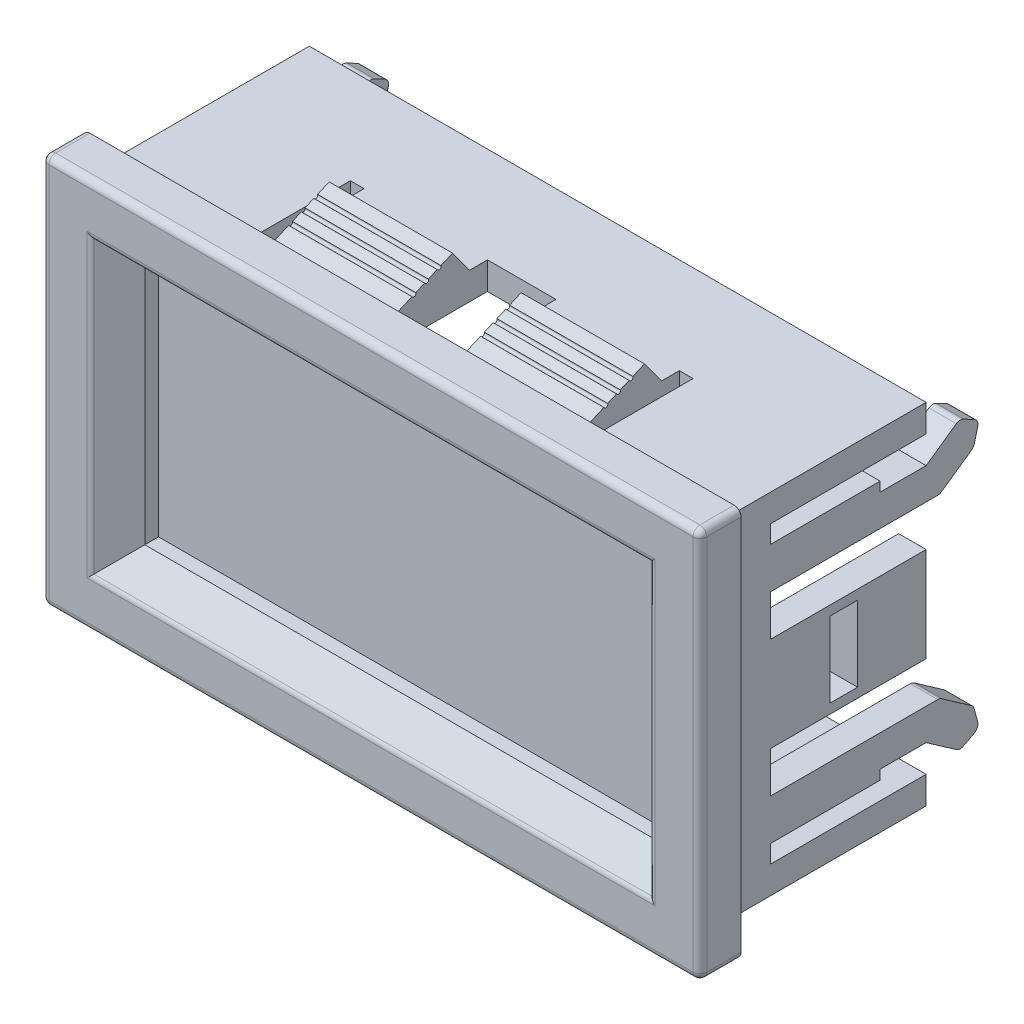
SolidWorks part; units mm, degrees
ref_plane "Front Plane" through (0, 0, 0) normal (0, 0, 1) x (1, 0, 0)
ref_plane "Top Plane" through (0, 0, 0) normal (0, 1, 0) x (1, 0, 0)
ref_plane "Right Plane" through (0, 0, 0) normal (1, 0, 0) x (0, 0, -1)
sketch "Sketch1" plane through (0, 0, 0) normal (0, 0, 1) x (1, 0, 0)
  line L0 (2, 23.5) -> (43, 23.5)
  line L1 (0, 0) -> (45, 0)
  line L2 (0, 0) -> (0, 25.5)
  line L3 (0, 25.5) -> (45, 25.5)
  line L4 (45, 0) -> (45, 25.5)
  line L5 (43, 2) -> (43, 23.5)
  line L6 (2, 2) -> (43, 2)
  line L7 (2, 2) -> (2, 23.5)
  dimension "D1" = 45
  dimension "D2" = 25.5
  dimension "D3" = 2
extrude "Boss-Extrude1" add sketch "Sketch1" along normal blind 15 contours L3 L4 L1 L2 | L0 L5 L6 L7
sketch "Sketch2" plane through (0, 0, 15) normal (0, 0, 1) x (1, 0, 0)
  line L4 (41, 21.5) -> (4, 21.5)
  line L5 (4, 21.5) -> (4, 4)
  line L9 (4, 4) -> (41, 4)
  line L10 (41, 4) -> (41, 21.5)
  line L11 (-1.5, 27) -> (-1.5, -1.5)
  line L12 (-1.5, -1.5) -> (46.5, -1.5)
  line L13 (46.5, -1.5) -> (46.5, 27)
  line L14 (46.5, 27) -> (-1.5, 27)
  line L15 (-1.5, 27) -> (-1.5, -1.5)
  line L16 (-1.5, -1.5) -> (46.5, -1.5)
  line L17 (46.5, -1.5) -> (46.5, 27)
  line L18 (46.5, 27) -> (-1.5, 27)
  dimension "D1" = 1.5
  dimension "D2" = 5.5
extrude "Boss-Extrude2" add sketch "Sketch2" along normal blind 3 contours L18 L15 L16 L17 | L4 L5 L9 L10
fillet "Fillet1" radius 0.5 4 edges at (46.5, 27, 16.5) (46.5, -1.5, 16.5) (-1.5, -1.5, 16.5) (-1.5, 27, 16.5)
fillet "Fillet2" radius 0.5 8 edges at (46.3536, -1.3536, 18) (-1.3536, -1.3536, 18) (-1.3536, 26.8536, 18) (46.3536, 26.8536, 18) (-1.5, 12.75, 18) (22.5, -1.5, 18) (22.5, 27, 18) (46.5, 12.75, 18)
chamfer "Chamfer1" distance 2 angle 45 4 edges at (41, 12.75, 18) (22.5, 21.5, 18) (4, 12.75, 18) (22.5, 4, 18)
fillet "Fillet3" radius 0.5 4 edges at (43, 12.75, 18) (22.5, 23.5, 18) (2, 12.75, 18) (22.5, 2, 18)
sketch "Sketch3" plane through (0, 0, 15) normal (0, 0, -1) x (-1, 0, 0)
  line L8 (-42, 3) -> (-3, 3)
  line L9 (-3, 3) -> (-3, 22.5)
  line L10 (-3, 22.5) -> (-42, 22.5)
  line L11 (-42, 22.5) -> (-42, 3)
  line L12 (-42, 3) -> (-3, 3)
  line L13 (-3, 3) -> (-3, 22.5)
  line L14 (-3, 22.5) -> (-42, 22.5)
  line L15 (-42, 22.5) -> (-42, 3)
  dimension "D1" = 1
extrude "Boss-Extrude3" add sketch "Sketch3" along normal blind 0.1
sketch "Sketch4" plane through (0, 0, 0) normal (-1, 0, 0) x (0, 0, 1)
  line L0 (0, 25.5) -> (0, 23.5)
  line L1 (0, 23.5) -> (11.3543, 23.5)
  line L2 (11.3543, 23.5) -> (11.3543, 22.2)
  line L3 (11.3543, 22.2) -> (3.3543, 22.2)
  line L4 (-1.0527, 21.5) -> (-1.0527, 19.2)
  line L5 (-1.0527, 19.2) -> (11.35, 19.2)
  line L6 (3.3543, 22.7727) -> (3.3543, 21.1169) construction
  line L7 (3.3543, 22.2) -> (3.3543, 21.5)
  line L8 (3.3543, 21.5) -> (-1.0527, 21.5)
  line L9 (-6.0086, 12.75) -> (7, 12.75) construction
  line L10 (15, 26.5) -> (15, -1) construction
  line L11 (11.35, 19.2) -> (11.35, 16.2)
  line L12 (11.35, 16.2) -> (-2.7404, 16.2)
  line L13 (-2.7404, 16.2) -> (-2.1337, 24.5086)
  line L14 (-2.1337, 24.5086) -> (0, 25.5)
  line L15 (3.3543, 2.7273) -> (3.3543, 4.3831) construction
  line L16 (-2.1337, 0.9914) -> (0, 0)
  line L17 (-2.7404, 9.3) -> (-2.1337, 0.9914)
  line L18 (11.35, 9.3) -> (-2.7404, 9.3)
  line L19 (11.35, 6.3) -> (11.35, 9.3)
  line L20 (3.3543, 4) -> (-1.0527, 4)
  line L21 (3.3543, 3.3) -> (3.3543, 4)
  line L22 (-1.0527, 6.3) -> (11.35, 6.3)
  line L23 (-1.0527, 4) -> (-1.0527, 6.3)
  line L24 (11.3543, 3.3) -> (3.3543, 3.3)
  line L25 (11.3543, 2) -> (11.3543, 3.3)
  line L26 (0, 2) -> (11.3543, 2)
  line L27 (0, 0) -> (0, 2)
  line L28 (0, 0) -> (0, 25.5) construction
  line L29 (5, 15.5) -> (7, 15.5)
  line L30 (5, 15.5) -> (5, 10)
  line L31 (5, 10) -> (7, 10)
  line L32 (7, 15.5) -> (7, 10)
  dimension "D1" = 2
  dimension "D2" = 1.3
  dimension "D3" = 8
  dimension "D4" = 0.7
  dimension "D5" = 3
  dimension "D6" = 3.65
  dimension "D7" = 3
  dimension "D8" = 12.75
  dimension "D9" = 5.5
  dimension "D10" = 2
  dimension "D11" = 5
extrude "Cut-Extrude1" cut sketch "Sketch4" against normal blind 7
ref_plane "Plane1" through (22.5, 0, 0) normal (1, 0, 0) x (0, 0, -1)
mirror "Mirror1" about plane through (22.5, 0, 0) normal (1, 0, 0) of "Cut-Extrude1"
sketch "Sketch5" plane through (0, 0, 0) normal (-1, 0, 0) x (0, 0, 1)
  line L0 (0, 21.5) -> (-2.2056, 23.0444)
  line L1 (0, 21.5) -> (3.3543, 21.5) construction
  line L2 (0, 19.2) -> (-0.8424, 19.2)
  line L3 (-1.1291, 19.2904) -> (-3.3085, 20.8165)
  line L4 (-3.5046, 21.0963) -> (-3.769, 22.0801)
  line L5 (-3.5222, 22.6506) -> (-2.7285, 23.0756)
  line L6 (-7.5626, 12.75) -> (3.2425, 12.75) construction
  line L7 (-3.5222, 2.8494) -> (-2.7285, 2.4244)
  line L8 (-3.5046, 4.4037) -> (-3.769, 3.4199)
  line L9 (-1.1291, 6.2096) -> (-3.3085, 4.6835)
  line L10 (0, 6.3) -> (-0.8424, 6.3)
  line L11 (0, 4) -> (-2.2056, 2.4556)
  line L12 (0, 21.5) -> (0, 19.2)
  line L13 (0, 4) -> (0, 6.3)
  arc A0 (-3.5222, 22.6506) -> (-3.769, 22.0801) centre (-3.2861, 22.2098) ccw
  arc A1 (-0.8424, 19.2) -> (-1.1291, 19.2904) centre (-0.8424, 19.7) cw
  arc A2 (-3.5046, 21.0963) -> (-3.3085, 20.8165) centre (-3.0218, 21.226) ccw
  arc A3 (-2.7285, 23.0756) -> (-2.2056, 23.0444) centre (-2.4924, 22.6348) cw
  arc A4 (-2.7285, 2.4244) -> (-2.2056, 2.4556) centre (-2.4924, 2.8652) ccw
  arc A5 (-3.5046, 4.4037) -> (-3.3085, 4.6835) centre (-3.0218, 4.274) cw
  arc A6 (-0.8424, 6.3) -> (-1.1291, 6.2096) centre (-0.8424, 5.8) ccw
  arc A7 (-3.5222, 2.8494) -> (-3.769, 3.4199) centre (-3.2861, 3.2902) cw
  point P15 (-1, 19.2)
  point P18 (-3.4575, 20.9207)
  point P21 (-2.4575, 23.2207)
  point P38 (-2.4575, 2.2793)
  point P39 (-3.4575, 4.5793)
  point P40 (-1, 6.3)
  dimension "D6" = 0.5
  dimension "D7" = 0.5
  dimension "D1" = 145
  dimension "D2" = 1
  dimension "D3" = 145
  dimension "D4" = 3
  dimension "D5" = 3
  dimension "D8" = 12.75
extrude "Boss-Extrude4" add sketch "Sketch5" against normal blind 2 contours L0 A3 L5 A0 L4 A2 L3 A1 L2 L12 | L9 A5 L8 A7 L7 A4 L11 L13 L10 A6
mirror "Mirror3" about plane through (22.5, 0, 0) normal (1, 0, 0) of "Boss-Extrude4"
sketch "Sketch6" plane through (0, 25.5, 0) normal (0, 1, 0) x (1, 0, 0)
  line L0 (0, -15) -> (45, -15) construction
  line L1 (35, -15) -> (10, -15)
  line L2 (35, -15) -> (35, -7)
  line L3 (35, -7) -> (10, -7)
  line L4 (10, -15) -> (10, -7)
  line L5 (45, -15) -> (45, 0) construction
  dimension "D1" = 10
  dimension "D2" = 25
  dimension "D3" = 8
extrude "Cut-Extrude4" cut sketch "Sketch6" against normal blind 2 contours L3 L4 L1 L2
ref_plane "Plane2" through (11, 0, 0) normal (1, 0, 0) x (0, 0, -1)
sketch "Sketch7" plane through (11, 0, 0) normal (1, 0, 0) x (0, 0, -1)
  line L0 (-7, 23.5) -> (-13.5, 23.5)
  line L1 (-13.5, 23.5) -> (-13.5, 25.5)
  line L2 (-13.5, 25.5) -> (-12.5044, 25.928)
  line L3 (-9.5457, 27.2) -> (-8.3, 25.5)
  line L4 (-8.3, 25.5) -> (-7, 25.5)
  line L5 (-7, 25.5) -> (-7, 23.5)
  line L6 (-15, 23.5) -> (-15, 25.5) construction
  line L7 (-15, 25.5) -> (-7, 25.5) construction
  line L8 (-11.3461, 27.2) -> (-7.8475, 27.2) construction
  line L9 (-11.3111, 26.441) -> (-10.667, 26.7179)
  line L10 (-10.3924, 26.836) -> (-9.5457, 27.2)
  line L11 (-12.2298, 26.0461) -> (-11.5857, 26.323)
  arc A0 (-10.667, 26.7179) -> (-10.3924, 26.836) centre (-10.5297, 26.777) ccw
  arc A1 (-11.5857, 26.323) -> (-11.3111, 26.441) centre (-11.4484, 26.3821) ccw
  arc A2 (-12.5044, 25.928) -> (-12.2298, 26.0461) centre (-12.3672, 25.9872) ccw
  dimension "D5" = 0.2989
  dimension "D1" = 2
  dimension "D2" = 1.5
  dimension "D3" = 1.3
  dimension "D4" = 1.7
  dimension "D6" = 23.263
  dimension "D7" = 3
extrude "Boss-Extrude5" add sketch "Sketch7" along normal blind 9
ref_plane "Plane3" through (22.5, 0, 0) normal (1, 0, 0) x (0, 0, -1)
mirror "Mirror4" about plane through (22.5, 0, 0) normal (1, 0, 0) of "Boss-Extrude5"
ref_plane "Plane4" through (0, 12.75, 0) normal (0, 1, 0) x (1, 0, 0)
mirror "Mirror5" about plane through (0, 12.75, 0) normal (0, 1, 0) of "Cut-Extrude4", "Boss-Extrude5", "Mirror4"
